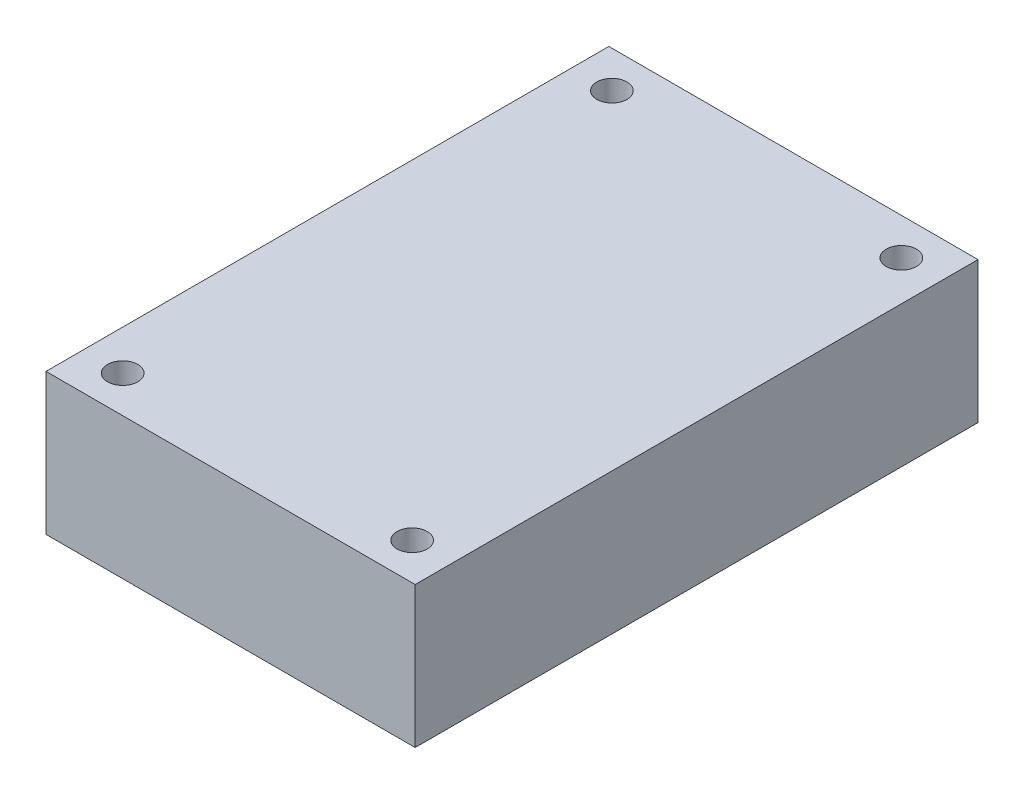
SolidWorks part; units mm, degrees
ref_plane "前视基准面" through (0, 0, 0) normal (0, 0, 1) x (1, 0, 0)
ref_plane "上视基准面" through (0, 0, 0) normal (0, 1, 0) x (1, 0, 0)
ref_plane "右视基准面" through (0, 0, 0) normal (1, 0, 0) x (0, 0, -1)
other "Configuration Table"
sketch "草图1" plane through (0, 0, 0) normal (0, 1, 0) x (1, 0, 0)
  line L1 (-18.3, 27.9) -> (18.3, 27.9)
  line L2 (-18.3, 27.9) -> (-18.3, -27.9)
  line L3 (-18.3, -27.9) -> (18.3, -27.9)
  line L4 (18.3, 27.9) -> (18.3, -27.9)
  line L5 (-18.3, 27.9) -> (18.3, -27.9) construction
  line L6 (-18.3, -27.9) -> (18.3, 27.9) construction
  point P0 (0, 0)
  dimension "D1" = 55.8
  dimension "D2" = 36.6
extrude "凸台-拉伸1" add sketch "草图1" along normal blind 14
sketch "草图3" plane through (0, 0, 0) normal (0, 1, 0) x (1, 0, 0)
  line L0 (0, 0) -> (21.1897, 0) construction
  line L1 (-14.35, 24.25) -> (14.35, 24.25) construction
  line L2 (-14.35, 24.25) -> (-14.35, -24.25) construction
  line L3 (-14.35, -24.25) -> (14.35, -24.25) construction
  line L4 (14.35, 24.25) -> (14.35, -24.25) construction
  line L5 (-14.35, 24.25) -> (14.35, -24.25) construction
  line L6 (-14.35, -24.25) -> (14.35, 24.25) construction
  line L7 (0, 0) -> (0, 28.746) construction
  circle A0 centre (-14.35, 24.25) radius 1.5
  circle A1 centre (-14.35, -24.25) radius 1.5
  circle A2 centre (14.35, -24.25) radius 1.5
  circle A3 centre (14.35, 24.25) radius 1.5
  point P0 (0, 0)
  dimension "D3" = 3
  dimension "D1" = 28.7
  dimension "D2" = 48.5
extrude "切除-拉伸1" cut sketch "草图3" along normal through all
